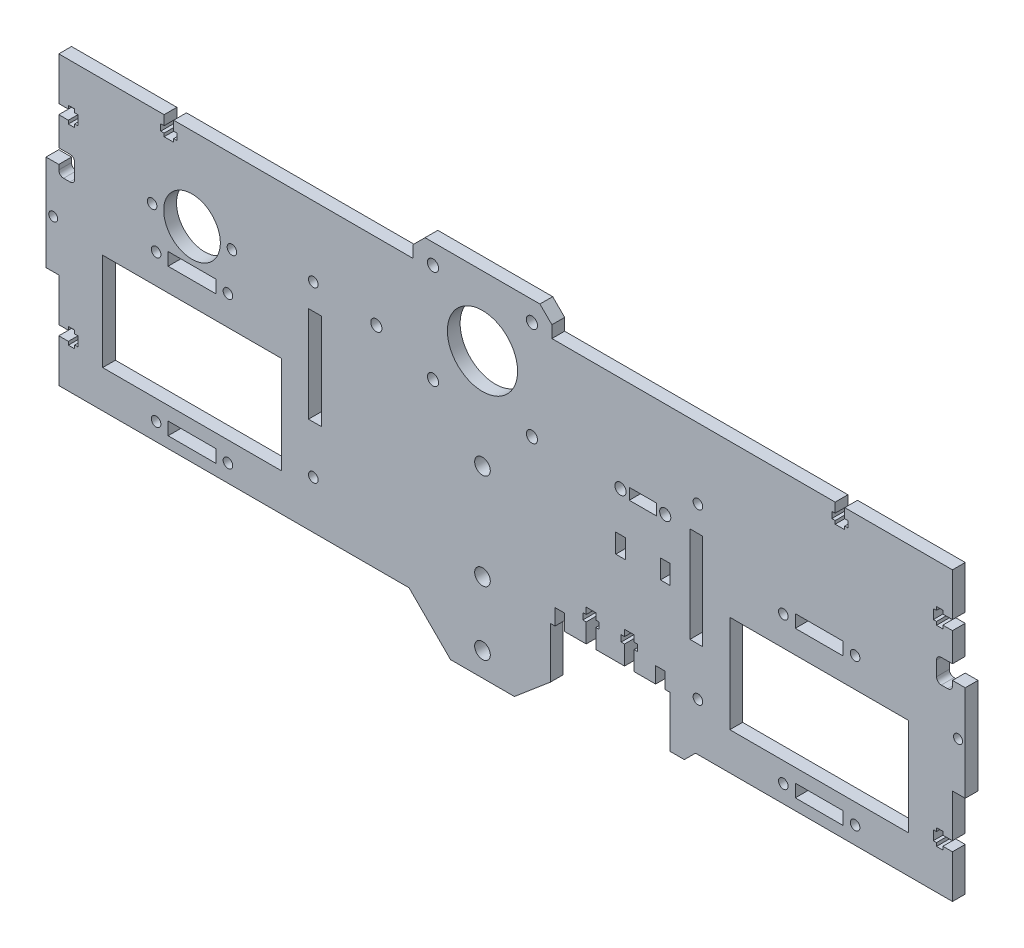
SolidWorks part; units mm, degrees
ref_plane "Спереди" through (0, 0, 0) normal (0, 0, 1) x (1, 0, 0)
ref_plane "Сверху" through (0, 0, 0) normal (0, 1, 0) x (1, 0, 0)
ref_plane "Справа" through (0, 0, 0) normal (1, 0, 0) x (0, 0, -1)
sketch "Эскиз1" plane through (0, 0, 0) normal (0, 0, 1) x (1, 0, 0)
  line L0 (81, 40.75) -> (76.5, 36.25) construction
  line L1 (-140, -45) -> (140, -45)
  line L2 (-140, -45) -> (-140, 45)
  line L3 (-140, 45) -> (140, 45)
  line L4 (140, -45) -> (140, 45)
  line L5 (-140, -45) -> (140, 45) construction
  line L6 (-140, 45) -> (140, -45) construction
  line L7 (-105.75, -37.5) -> (-90.75, -37.5)
  line L8 (-105.75, -37.5) -> (-105.75, -41.5)
  line L9 (-105.75, -41.5) -> (-90.75, -41.5)
  line L10 (-90.75, -37.5) -> (-90.75, -41.5)
  line L11 (-105.75, -37.5) -> (-90.75, -41.5) construction
  line L12 (-105.75, -41.5) -> (-90.75, -37.5) construction
  line L13 (-105.75, 4.5) -> (-90.75, 4.5)
  line L14 (-105.75, 4.5) -> (-105.75, 8.5)
  line L15 (-105.75, 8.5) -> (-90.75, 8.5)
  line L16 (-90.75, 4.5) -> (-90.75, 8.5)
  line L17 (-105.75, 4.5) -> (-90.75, 8.5) construction
  line L18 (-105.75, 8.5) -> (-90.75, 4.5) construction
  line L19 (-126.25, -33.25) -> (-70.25, -33.25)
  line L20 (-126.25, -33.25) -> (-126.25, -2.75)
  line L21 (-126.25, -2.75) -> (-70.25, -2.75)
  line L22 (-70.25, -33.25) -> (-70.25, -2.75)
  line L23 (-126.25, -33.25) -> (-70.25, -2.75) construction
  line L24 (-126.25, -2.75) -> (-70.25, -33.25) construction
  line L25 (115.5, -2.75) -> (81, -2.75) construction
  line L26 (120, 1.75) -> (120, 36.25) construction
  line L27 (115.5, 40.75) -> (81, 40.75) construction
  line L28 (76.5, 1.75) -> (76.5, 36.25) construction
  line L29 (120, -2.75) -> (76.5, 40.75) construction
  line L30 (120, 40.75) -> (76.5, -2.75) construction
  line L31 (120, 36.25) -> (115.5, 40.75) construction
  line L32 (120, 1.75) -> (115.5, -2.75) construction
  line L33 (81, -2.75) -> (76.5, 1.75) construction
  line L34 (0, -55) -> (0, 55) construction
  line L35 (126.25, -2.75) -> (70.25, -33.25) construction
  line L36 (126.25, -33.25) -> (70.25, -2.75) construction
  line L37 (105.75, 8.5) -> (90.75, 4.5) construction
  line L38 (105.75, 4.5) -> (90.75, 8.5) construction
  line L39 (105.75, -41.5) -> (90.75, -37.5) construction
  line L40 (105.75, -37.5) -> (90.75, -41.5) construction
  line L41 (70.25, -33.25) -> (70.25, -2.75)
  line L42 (126.25, -2.75) -> (70.25, -2.75)
  line L43 (126.25, -33.25) -> (126.25, -2.75)
  line L44 (126.25, -33.25) -> (70.25, -33.25)
  line L45 (90.75, 4.5) -> (90.75, 8.5)
  line L46 (105.75, 8.5) -> (90.75, 8.5)
  line L47 (105.75, 4.5) -> (105.75, 8.5)
  line L48 (105.75, 4.5) -> (90.75, 4.5)
  line L49 (90.75, -37.5) -> (90.75, -41.5)
  line L50 (105.75, -41.5) -> (90.75, -41.5)
  line L51 (105.75, -37.5) -> (105.75, -41.5)
  line L52 (105.75, -37.5) -> (90.75, -37.5)
  line L53 (-109.5, 6.5) -> (-87, 6.5) construction
  line L54 (-109.5, -39.5) -> (-87, -39.5) construction
  line L55 (135, 12) -> (135, 19.5)
  line L56 (-140, 12) -> (-135, 12)
  line L57 (-140, 12) -> (-140, 19.5)
  line L58 (-140, 19.5) -> (-135, 19.5)
  line L59 (-135, 12) -> (-135, 19.5)
  line L61 (102.2, 40) -> (107.3, 40) construction
  line L62 (102.2, 40) -> (102.2, 42) construction
  line L63 (107.3, 40) -> (107.3, 42) construction
  line L64 (102.2, 42) -> (107.3, 42) construction
  line L66 (-135, -27.45) -> (-135, -28.5) construction
  line L67 (-135, -28.5) -> (-134, -28.5) construction
  line L68 (-134, -28.5) -> (-134, -31.5) construction
  line L69 (-134, -31.5) -> (-135, -31.5) construction
  line L70 (-135, -31.5) -> (-135, -32.55) construction
  line L71 (-135, -32.55) -> (-137, -32.55) construction
  line L72 (-137, -32.55) -> (-137, -31.5) construction
  line L73 (-137, -31.5) -> (-140, -31.5) construction
  line L74 (-140, -31.5) -> (-140, -45) construction
  line L75 (-140, -45) -> (140, -45) construction
  line L76 (140, -45) -> (140, -31.5) construction
  line L77 (140, -31.5) -> (137, -31.5) construction
  line L78 (137, -31.5) -> (137, -32.55) construction
  line L79 (137, -32.55) -> (135, -32.55) construction
  line L80 (135, -32.55) -> (135, -31.5) construction
  line L81 (135, -31.5) -> (134, -31.5) construction
  line L82 (134, -31.5) -> (134, -28.5) construction
  line L83 (134, -28.5) -> (135, -28.5) construction
  line L84 (135, -28.5) -> (135, -27.45) construction
  line L85 (135, -27.45) -> (137, -27.45) construction
  line L86 (137, -27.45) -> (137, -28.5) construction
  line L87 (137, -28.5) -> (140, -28.5) construction
  line L88 (140, -28.5) -> (140, -15) construction
  line L89 (140, -15) -> (144, -15) construction
  line L90 (144, -15) -> (144, 15) construction
  line L91 (144, 15) -> (140, 15) construction
  line L92 (140, 15) -> (140, 28.5) construction
  line L93 (140, 28.5) -> (137, 28.5) construction
  line L94 (137, 28.5) -> (137, 27.45) construction
  line L95 (137, 27.45) -> (135, 27.45) construction
  line L96 (135, 27.45) -> (135, 28.5) construction
  line L97 (135, 28.5) -> (134, 28.5) construction
  line L98 (134, 28.5) -> (134, 31.5) construction
  line L99 (134, 31.5) -> (135, 31.5) construction
  line L100 (135, 31.5) -> (135, 32.55) construction
  line L101 (135, 32.55) -> (137, 32.55) construction
  line L102 (137, 32.55) -> (137, 31.5) construction
  line L103 (137, 31.5) -> (140, 31.5) construction
  line L105 (140, 19.5) -> (135, 19.5)
  line L120 (103.25, 45) -> (106.25, 45) construction
  line L122 (-108.05, 40) -> (-102.95, 40) construction
  line L124 (-108.05, 40) -> (-108.05, 42) construction
  line L136 (-102.95, 40) -> (-102.95, 42) construction
  line L148 (140, 12) -> (140, 19.5)
  line L151 (-140, 31.5) -> (-137, 31.5) construction
  line L152 (-137, 31.5) -> (-137, 32.55) construction
  line L153 (-137, 32.55) -> (-135, 32.55) construction
  line L154 (-135, 32.55) -> (-135, 31.5) construction
  line L155 (-135, 31.5) -> (-134, 31.5) construction
  line L156 (-134, 31.5) -> (-134, 28.5) construction
  line L157 (-134, 28.5) -> (-135, 28.5) construction
  line L158 (-135, 28.5) -> (-135, 27.45) construction
  line L159 (-135, 27.45) -> (-137, 27.45) construction
  line L160 (-137, 27.45) -> (-137, 28.5) construction
  line L161 (-137, 28.5) -> (-140, 28.5) construction
  line L162 (-140, 28.5) -> (-140, 15) construction
  line L163 (-140, 15) -> (-144, 15) construction
  line L164 (-144, 15) -> (-144, -15) construction
  line L165 (-144, -15) -> (-140, -15) construction
  line L166 (-140, -15) -> (-140, -28.5) construction
  line L167 (-140, -28.5) -> (-137, -28.5) construction
  line L168 (-137, -28.5) -> (-137, -27.45) construction
  line L169 (-137, -27.45) -> (-135, -27.45) construction
  line L170 (14.5, 12.75) -> (14.5, 48.75)
  line L171 (10.75, 9) -> (14.5, 12.75)
  line L172 (-25.25, 9) -> (10.75, 9)
  line L173 (-29, 12.75) -> (-25.25, 9)
  line L174 (-29, 12.75) -> (-29, 48.75)
  line L175 (10.75, 52.5) -> (14.5, 48.75)
  line L176 (-25.25, 52.5) -> (10.75, 52.5)
  line L177 (-29, 48.75) -> (-25.25, 52.5)
  line L178 (-107, 45) -> (-104, 45) construction
  line L180 (-108.05, 42) -> (-102.95, 42) construction
  line L181 (-135, -27.45) -> (-135, -28.5)
  line L182 (-135, -28.5) -> (-134, -28.5)
  line L183 (-134, -28.5) -> (-134, -31.5)
  line L184 (-134, -31.5) -> (-135, -31.5)
  line L185 (-135, -31.5) -> (-135, -32.55)
  line L186 (-135, -32.55) -> (-137, -32.55)
  line L187 (-137, -32.55) -> (-137, -31.5)
  line L188 (-137, -31.5) -> (-140, -31.5)
  line L189 (-140, -31.5) -> (-140, -45)
  line L190 (-140, -45) -> (140, -45)
  line L191 (140, -45) -> (140, -31.5)
  line L192 (140, -31.5) -> (137, -31.5)
  line L193 (137, -31.5) -> (137, -32.55)
  line L194 (137, -32.55) -> (135, -32.55)
  line L195 (135, -32.55) -> (135, -31.5)
  line L196 (135, -31.5) -> (134, -31.5)
  line L197 (134, -31.5) -> (134, -28.5)
  line L198 (134, -28.5) -> (135, -28.5)
  line L199 (135, -28.5) -> (135, -27.45)
  line L200 (135, -27.45) -> (137, -27.45)
  line L201 (137, -27.45) -> (137, -28.5)
  line L202 (137, -28.5) -> (140, -28.5)
  line L203 (140, -28.5) -> (140, -15)
  line L204 (140, -15) -> (144, -15)
  line L205 (144, -15) -> (144, 15)
  line L206 (144, 15) -> (140, 15)
  line L207 (140, 15) -> (140, 28.5)
  line L208 (140, 28.5) -> (137, 28.5)
  line L209 (137, 28.5) -> (137, 27.45)
  line L210 (137, 27.45) -> (135, 27.45)
  line L211 (135, 27.45) -> (135, 28.5)
  line L212 (135, 28.5) -> (134, 28.5)
  line L213 (134, 28.5) -> (134, 31.5)
  line L214 (134, 31.5) -> (135, 31.5)
  line L215 (135, 31.5) -> (135, 32.55)
  line L216 (135, 32.55) -> (137, 32.55)
  line L217 (137, 32.55) -> (137, 31.5)
  line L218 (137, 31.5) -> (140, 31.5)
  line L266 (-140, 31.5) -> (-137, 31.5)
  line L267 (-137, 31.5) -> (-137, 32.55)
  line L268 (-137, 32.55) -> (-135, 32.55)
  line L269 (-135, 32.55) -> (-135, 31.5)
  line L270 (-135, 31.5) -> (-134, 31.5)
  line L271 (-134, 31.5) -> (-134, 28.5)
  line L272 (-134, 28.5) -> (-135, 28.5)
  line L273 (-135, 28.5) -> (-135, 27.45)
  line L274 (-135, 27.45) -> (-137, 27.45)
  line L275 (-137, 27.45) -> (-137, 28.5)
  line L276 (-137, 28.5) -> (-140, 28.5)
  line L277 (-140, 28.5) -> (-140, 15)
  line L278 (-140, 15) -> (-144, 15)
  line L279 (-144, 15) -> (-144, -15)
  line L280 (-144, -15) -> (-140, -15)
  line L281 (-140, -15) -> (-140, -28.5)
  line L282 (-140, -28.5) -> (-137, -28.5)
  line L283 (-137, -28.5) -> (-137, -27.45)
  line L284 (-137, -27.45) -> (-135, -27.45)
  line L286 (-131, 31.5) -> (-131, 28.5)
  line L288 (131, 31.5) -> (131, 28.5)
  line L290 (103.25, 39) -> (106.25, 39)
  line L291 (102.2, 40) -> (107.3, 40)
  line L292 (102.2, 40) -> (102.2, 42)
  line L293 (107.3, 40) -> (107.3, 42)
  line L294 (102.2, 42) -> (107.3, 42)
  line L295 (103.25, 45) -> (103.25, 39)
  line L296 (103.25, 45) -> (106.25, 45)
  line L297 (106.25, 45) -> (106.25, 39)
  line L298 (-108.05, 40) -> (-102.95, 40)
  line L299 (-108.05, 40) -> (-108.05, 42)
  line L300 (-7.25, 52.5) -> (-7.25, 9) construction
  line L310 (-107, 39) -> (-104, 39)
  line L311 (-102.95, 40) -> (-102.95, 42)
  line L312 (-107, 45) -> (-104, 45)
  line L314 (-104, 45) -> (-104, 39)
  line L315 (-108.05, 42) -> (-102.95, 42)
  line L316 (-107, 45) -> (-107, 39)
  line L317 (140, 12) -> (135, 12)
  circle A8 centre (98.25, 19) radius 6 construction
  circle A9 centre (-98.25, 19) radius 8.875
  circle A10 centre (-85.75, 19) radius 1.5
  circle A11 centre (-110.75, 19) radius 1.5
  circle A15 centre (-141.75, 0) radius 1.4
  circle A16 centre (141.75, 0) radius 1.4
  circle A17 centre (-40.5, 21.1) radius 1.75
  circle A26 centre (-87, 6.5) radius 1.5
  circle A27 centre (-109.5, 6.5) radius 1.5
  circle A28 centre (-109.5, -39.5) radius 1.5
  circle A29 centre (-87, -39.5) radius 1.5
  circle A30 centre (87, -39.5) radius 1.5
  circle A31 centre (109.5, -39.5) radius 1.5
  circle A32 centre (109.5, 6.5) radius 1.5
  circle A33 centre (87, 6.5) radius 1.5
  point P0 (0, 0)
  point P5 (-98.25, -39.5)
  point P11 (-98.25, 6.5)
  point P16 (-98.25, -18)
  point P28 (98.25, 19)
  point P54 (-98.25, 6.5)
  point P58 (-98.25, -2.75)
  point P63 (98.25, -18)
  point P64 (98.25, 6.5)
  point P65 (98.25, -39.5)
  point P66 (-98.25, -39.5)
  point P159 (-144, 0)
  point P175 (-40.5, -35.103)
  dimension "D10" = 3
  dimension "D23" = 2
  dimension "D24" = 12
  dimension "D25" = 17.75
  dimension "D30" = 3
  dimension "D32" = 9
  dimension "D33" = 23.9
  dimension "D44" = 2.8
  dimension "D34" = 3.5
  dimension "D1" = 280
  dimension "D2" = 90
  dimension "D3" = 3.5
  dimension "D4" = 15
  dimension "D5" = 4
  dimension "D6" = 42
  dimension "D7" = 11.75
  dimension "D8" = 30.5
  dimension "D9" = 56
  dimension "D11" = 43.5
  dimension "D12" = 4.5
  dimension "D13" = 4.5
  dimension "D14" = 4.5
  dimension "D15" = 4.5
  dimension "D16" = 4.5
  dimension "D17" = 4.5
  dimension "D18" = 4.5
  dimension "D19" = 4.5
  dimension "D20" = 64
  dimension "D21" = 98.25
  dimension "D22" = 22.5
  dimension "D26" = 22.5
  dimension "D27" = 2
  dimension "D28" = 98.25
  dimension "D29" = 12.5
  dimension "D31" = 12.5
  dimension "D35" = 36
  dimension "D36" = 36
  dimension "D37" = 3.75
  dimension "D38" = 3.75
  dimension "D39" = 29
  dimension "D40" = 9
  dimension "D41" = 5
  dimension "D42" = 7.5
  dimension "D43" = 3
  dimension "D45" = 2.25
  dimension "D46" = 6
extrude "Бобышка-Вытянуть1" add sketch "Эскиз1" along normal blind 4 contours L316 L3 L2 L266 L267 L268 L269 L270 L271 L272 L273 L274 L275 L276 L282 L283 L284 L181 L182 L20 L21 L22 L19 L184 L185 L186 L187 L188 L1 L4 L192 L193 L194 L195 L196 L43 L44 L41 L42 L198 | L177 L174 L3 L170 L175 L176 | L174 L173 L172 L171 L170 L3 | L205 L206 L4 L204 | L279 L280 L2 L278
sketch "Эскиз2" plane through (0, 0, 4) normal (0, 0, 1) x (1, 0, 0)
  line L0 (140, 45) -> (144, 45) construction
  line L1 (144, 45) -> (144, 15) construction
  line L2 (140, 45) -> (140, 15) construction
  line L54 (69.5, 45) -> (69.5, 49) construction
  line L60 (69.5, 45) -> (89.5, 45) construction
  line L62 (140, 15) -> (144, 15) construction
  line L63 (144, 15) -> (140, 15) construction
  line L64 (144, 15) -> (144, -15) construction
  line L65 (140, 15) -> (140, -15) construction
  line L67 (69.5, 49) -> (89.5, 49) construction
  line L73 (89.5, 45) -> (89.5, 49) construction
  line L75 (140, -15) -> (144, -15) construction
  line L76 (140, -45) -> (140, -15) construction
  line L77 (140, -45) -> (144, -45) construction
  line L78 (144, -45) -> (144, -15) construction
  line L79 (144, -15) -> (140, -15) construction
  line L80 (-140, 45) -> (-140, 15) construction
  line L81 (-144, 45) -> (-144, 15) construction
  line L82 (-140, 45) -> (-144, 45) construction
  line L83 (-140, 15) -> (-144, 15) construction
  line L84 (-144, 15) -> (-140, 15) construction
  line L85 (-140, 15) -> (-140, -15) construction
  line L86 (-144, 15) -> (-144, -15) construction
  line L87 (-140, -15) -> (-144, -15) construction
  line L88 (-144, -45) -> (-144, -15) construction
  line L89 (-140, -45) -> (-144, -45) construction
  line L90 (-140, -45) -> (-140, -15) construction
  line L91 (-144, -15) -> (-140, -15) construction
  line L92 (140, 45) -> (144, 45)
  line L93 (144, 45) -> (144, 15)
  line L94 (140, 45) -> (140, 15)
  line L106 (140, 15) -> (144, 15)
  line L107 (144, 15) -> (140, 15)
  line L108 (144, 15) -> (144, -15)
  line L109 (140, 15) -> (140, -15)
  line L119 (140, -15) -> (144, -15)
  line L120 (140, -45) -> (140, -15)
  line L121 (140, -45) -> (144, -45)
  line L122 (144, -45) -> (144, -15)
  line L123 (144, -15) -> (140, -15)
  line L124 (-140, 45) -> (-140, 15)
  line L125 (-144, 45) -> (-144, 15)
  line L126 (-140, 45) -> (-144, 45)
  line L127 (-140, 15) -> (-144, 15)
  line L128 (-144, 15) -> (-140, 15)
  line L129 (-140, 15) -> (-140, -15)
  line L130 (-144, 15) -> (-144, -15)
  line L131 (-140, -15) -> (-144, -15)
  line L132 (-144, -45) -> (-144, -15)
  line L133 (-140, -45) -> (-144, -45)
  line L134 (-140, -45) -> (-140, -15)
  line L135 (-144, -15) -> (-140, -15)
  line L136 (120, 45) -> (120, 49) construction
  line L137 (140, 45) -> (120, 45) construction
  line L138 (140, 45) -> (140, 49) construction
  line L139 (140, 49) -> (120, 49) construction
  line L140 (-140, 45) -> (-140, 49) construction
  line L141 (-140, 45) -> (-120, 45) construction
  line L142 (-120, 45) -> (-120, 49) construction
  line L143 (-140, 49) -> (-120, 49) construction
  line L144 (-71, 45) -> (-71, 49) construction
  line L145 (-71, 49) -> (-91, 49) construction
  line L146 (-91, 45) -> (-91, 49) construction
  line L147 (-71, 45) -> (-91, 45) construction
  line L148 (69.5, 45) -> (69.5, 49)
  line L149 (69.5, 45) -> (89.5, 45)
  line L150 (69.5, 49) -> (89.5, 49)
  line L151 (89.5, 45) -> (89.5, 49)
  line L152 (120, 45) -> (120, 49)
  line L153 (140, 45) -> (120, 45)
  line L154 (140, 45) -> (140, 49)
  line L155 (140, 49) -> (120, 49)
  line L156 (-140, 45) -> (-140, 49)
  line L157 (-140, 45) -> (-120, 45)
  line L158 (-120, 45) -> (-120, 49)
  line L159 (-140, 49) -> (-120, 49)
  line L160 (-71, 45) -> (-71, 49)
  line L161 (-71, 49) -> (-91, 49)
  line L162 (-91, 45) -> (-91, 49)
  line L163 (-71, 45) -> (-91, 45)
  circle A17 centre (-141.75, -30) radius 1.4
  circle A18 centre (-141.75, -30) radius 1.4
  circle A19 centre (141.75, -30) radius 1.4
  circle A20 centre (141.75, -30) radius 1.4
  circle A21 centre (141.75, 30) radius 1.4
  circle A22 centre (141.75, 30) radius 1.4
  circle A23 centre (-141.75, 0) radius 1.4
  circle A24 centre (-141.75, 0) radius 1.4
  circle A29 centre (-141.75, 30) radius 1.4
  circle A30 centre (-141.75, 30) radius 1.4
  circle A35 centre (141.75, 0) radius 1.4
  circle A36 centre (141.75, 0) radius 1.4
  circle A142 centre (79.5, 46.75) radius 1.4 construction
  circle A143 centre (130, 46.75) radius 1.4 construction
  circle A144 centre (-130, 46.75) radius 1.4 construction
  circle A145 centre (-81, 46.75) radius 1.4 construction
  circle A146 centre (79.5, 46.75) radius 1.4
  circle A147 centre (130, 46.75) radius 1.4
  circle A148 centre (-130, 46.75) radius 1.4
  circle A149 centre (-81, 46.75) radius 1.4
  dimension "D5" = 0
  dimension "D6" = 0
  dimension "D7" = 0
  dimension "D8" = 0
  dimension "D11" = 0
  dimension "D14" = 0
extrude "Бобышка-Вытянуть2" add sketch "Эскиз2" against normal through all
sketch "Эскиз3" plane through (0, 0, 4) normal (0, 0, 1) x (1, 0, 0)
  line L0 (-25.25, 52.5) -> (10.75, 52.5) construction
  line L1 (-140, -45) -> (140, -45) construction
  line L4 (140, -45) -> (140, -31.5) construction
  line L18 (-22.75, 46.25) -> (8.25, 46.25) construction
  line L19 (-22.75, 46.25) -> (-22.75, 15.25) construction
  line L20 (-22.75, 15.25) -> (8.25, 15.25) construction
  line L21 (8.25, 46.25) -> (8.25, 15.25) construction
  line L24 (14, -45) -> (51.5, -45)
  line L25 (14, -45) -> (14, -32.5)
  line L26 (14, -32.5) -> (51.5, -32.5)
  line L27 (51.5, -45) -> (51.5, -32.5)
  line L32 (18.5, -32.5) -> (18.5, -27.5)
  line L33 (50, -32.5) -> (47, -32.5)
  line L35 (50, -32.5) -> (50, -27.5)
  line L36 (50, -27.5) -> (47, -27.5)
  line L39 (47, -32.5) -> (47, -27.5)
  line L40 (15.5, -27.5) -> (18.5, -27.5)
  line L41 (32.75, -32.5) -> (32.75, -19.9047) construction
  line L42 (25.25, -32.5) -> (28.25, -32.5)
  line L43 (25.25, -32.5) -> (25.25, -22.5)
  line L44 (25.25, -22.5) -> (28.25, -22.5)
  line L45 (28.25, -32.5) -> (28.25, -22.5)
  line L46 (24.2, -26.5) -> (29.3, -26.5)
  line L47 (24.2, -26.5) -> (24.2, -24.5)
  line L48 (24.2, -24.5) -> (29.3, -24.5)
  line L49 (29.3, -26.5) -> (29.3, -24.5)
  line L50 (24.2, -26.5) -> (29.3, -24.5) construction
  line L51 (24.2, -24.5) -> (29.3, -26.5) construction
  line L52 (41.3, -24.5) -> (36.2, -26.5) construction
  line L53 (41.3, -26.5) -> (36.2, -24.5) construction
  line L54 (36.2, -26.5) -> (36.2, -24.5)
  line L55 (41.3, -24.5) -> (36.2, -24.5)
  line L56 (41.3, -26.5) -> (41.3, -24.5)
  line L57 (41.3, -26.5) -> (36.2, -26.5)
  line L58 (37.25, -32.5) -> (37.25, -22.5)
  line L59 (40.25, -22.5) -> (37.25, -22.5)
  line L60 (40.25, -32.5) -> (40.25, -22.5)
  line L61 (40.25, -32.5) -> (37.25, -32.5)
  line L62 (15.5, -32.5) -> (15.5, -27.5)
  line L63 (15.5, -32.5) -> (18.5, -32.5)
  circle A4 centre (8.25, 15.25) radius 1.75
  circle A5 centre (-22.75, 15.25) radius 1.75
  circle A6 centre (8.25, 46.25) radius 1.75
  circle A7 centre (-22.75, 46.25) radius 1.75
  circle A11 centre (-7.25, 30.75) radius 11
  point P2 (-7.25, 52.5)
  point P36 (-7.25, 46.25)
  point P45 (8.25, 30.75)
  point P81 (26.75, -22.5)
  point P83 (26.75, -25.5)
  point P103 (38.75, -25.5)
  dimension "D5" = 3.5
  dimension "D7" = 22
  dimension "D3" = 88.5
  dimension "D4" = 6.25
  dimension "D6" = 31
  dimension "D9" = 37.5
  dimension "D10" = 12.5
  dimension "D12" = 3
  dimension "D13" = 10
  dimension "D14" = 2
  dimension "D15" = 5.1
  dimension "D16" = 2
  dimension "D17" = 4.5
  dimension "D18" = 5
  dimension "D19" = 3
  dimension "D20" = 1.5
extrude "Вырез-Вытянуть1" cut sketch "Эскиз3" against normal through all
sketch "Эскиз4" plane through (0, 0, 4) normal (0, 0, 1) x (1, 0, 0)
  line L0 (2.75, 6.5) -> (2.75, -60.5) construction
  line L1 (2.75, -45) -> (-17.25, -45)
  line L2 (2.75, -45) -> (2.75, -58)
  line L3 (2.75, -58) -> (-17.25, -58)
  line L4 (-17.25, -45) -> (-17.25, -58)
  line L6 (14, -48.5) -> (2.75, -58)
  line L7 (14, -45) -> (9.5, -45)
  line L8 (14, -45) -> (14, -48.5)
  line L9 (14, -48.5) -> (9.5, -48.5)
  line L10 (9.5, -45) -> (9.5, -48.5)
  line L11 (9.5, -45) -> (2.75, -45)
  line L12 (-140, -45) -> (14, -45) construction
  line L13 (51.5, -45) -> (140, -45) construction
  line L14 (56, -45) -> (56, -48.5)
  line L15 (51.5, -48.5) -> (56, -48.5)
  line L16 (51.5, -45) -> (51.5, -48.5)
  line L17 (51.5, -45) -> (56, -45)
  line L18 (56, -48.5) -> (59.5, -45)
  line L20 (-17.25, -58) -> (-30.25, -45)
  line L21 (-17.25, -45) -> (-30.25, -45)
  line L22 (59.5, -45) -> (51.5, -45)
  circle A1 centre (-7.25, -50.5) radius 2.45
  dimension "D1" = 45
  dimension "D2" = 45
  dimension "D3" = 5.5
  dimension "D4" = 13
  dimension "D5" = 20
extrude "Бобышка-Вытянуть3" add sketch "Эскиз4" against normal through all contours L1 L4 L3 L2 | L10 L11 L2 L6 L9 | L7 L10 L9 L8 | L17 L16 L15 L14 | L18 L22 L14 | L4 L21 L20
sketch "Эскиз5" plane through (0, 0, 4) normal (0, 0, 1) x (1, 0, 0)
  line L0 (-140, -45) -> (-30.25, -45) construction
  line L1 (140, 1.5) -> (140, 15) construction
  line L2 (36, 15) -> (50, 15) construction
  line L3 (38.75, 13.25) -> (47.25, 13.25)
  line L4 (38.75, 13.25) -> (38.75, 16.75)
  line L5 (38.75, 16.75) -> (47.25, 16.75)
  line L6 (47.25, 13.25) -> (47.25, 16.75)
  line L7 (38.75, 13.25) -> (47.25, 16.75) construction
  line L8 (38.75, 16.75) -> (47.25, 13.25) construction
  line L9 (-59.75, 45) -> (-59.75, 15) construction
  line L11 (-59.75, 15) -> (-59.75, -15) construction
  line L12 (-59.75, -15) -> (-59.75, -45) construction
  line L13 (34.5, -3.5) -> (37.5, -3.5)
  line L14 (-59.75, 45) -> (-59.75, 35) construction
  line L15 (-59.75, 35) -> (-59.75, 25) construction
  line L16 (-59.75, 25) -> (-59.75, 15) construction
  line L17 (-61.75, 0) -> (-57.75, 0) construction
  line L18 (-61.75, -15) -> (-57.75, -15)
  line L19 (-61.75, -15) -> (-61.75, 15)
  line L20 (-61.75, 15) -> (-57.75, 15)
  line L21 (-57.75, -15) -> (-57.75, 15)
  line L22 (-61.75, -15) -> (-57.75, 15) construction
  line L23 (-61.75, 15) -> (-57.75, -15) construction
  line L24 (-66.75, -14.5) -> (-66.75, -10.8) construction
  line L25 (0, 0) -> (0, 20.9914) construction
  line L26 (61.75, 15) -> (57.75, -15) construction
  line L27 (61.75, -15) -> (57.75, 15) construction
  line L28 (61.75, 0) -> (57.75, 0) construction
  line L32 (59.5, -45) -> (140, -45) construction
  line L33 (59.75, 15) -> (59.75, -15) construction
  line L35 (57.75, -15) -> (57.75, 15)
  line L36 (61.75, 15) -> (57.75, 15)
  line L37 (61.75, -15) -> (61.75, 15)
  line L38 (61.75, -15) -> (57.75, -15)
  line L39 (0, -2.2) -> (0, 2.2) construction
  line L40 (60.25, 45) -> (60.25, 15) construction
  line L41 (2.2, 0) -> (-2.2, 0) construction
  line L42 (34.5, -3.5) -> (34.5, 2.5)
  line L43 (14.5, 45) -> (103.25, 45) construction
  line L44 (-104, 45) -> (-29, 45) construction
  line L45 (34.5, 2.5) -> (37.5, 2.5)
  line L46 (37.5, -3.5) -> (37.5, 2.5)
  line L47 (34.5, -3.5) -> (37.5, 2.5) construction
  line L48 (34.5, 2.5) -> (37.5, -3.5) construction
  line L49 (51.5, -3.5) -> (48.5, -3.5)
  line L50 (51.5, -3.5) -> (51.5, 2.5)
  line L51 (51.5, 2.5) -> (48.5, 2.5)
  line L52 (48.5, -3.5) -> (48.5, 2.5)
  line L53 (51.5, -3.5) -> (48.5, 2.5) construction
  line L54 (51.5, 2.5) -> (48.5, -3.5) construction
  circle A0 centre (-7.25, -30.5) radius 2.45 construction
  circle A1 centre (-7.25, -0.5) radius 2.45 construction
  circle A2 centre (-7.25, -30.5) radius 2.45
  circle A3 centre (-7.25, -0.5) radius 2.45
  circle A4 centre (36, 15) radius 1.75
  circle A5 centre (50, 15) radius 1.75
  circle A18 centre (60.25, 30) radius 1.5
  circle A19 centre (-60.25, 30) radius 1.5
  circle A20 centre (60.25, -30) radius 1.5
  circle A21 centre (-60.25, -30) radius 1.5
  circle A22 centre (60.25, 23) radius 1.5
  circle A23 centre (-60.25, 23) radius 1.5
  point P10 (43, 15)
  point P18 (43, 15)
  point P23 (36, -0.5)
  point P35 (-59.75, 0)
  point P66 (59.75, 0)
  point P77 (50, -0.5)
  dimension "D2" = 3.5
  dimension "D8" = 2.5
  dimension "D13" = 8
  dimension "D12" = 3
  dimension "D1" = 14
  dimension "D3" = 60
  dimension "D4" = 90
  dimension "D5" = 8.5
  dimension "D6" = 3.5
  dimension "D7" = 12.5
  dimension "D9" = 4
  dimension "D10" = 30
  dimension "D11" = 5
  dimension "D14" = 6
  dimension "D15" = 3
extrude "Вырез-Вытянуть2" cut sketch "Эскиз5" against normal through all contours A3 | A2 | A21 | L18 L21 L20 L19 | A23 | A22 | L38 L37 L36 L35 | A20 | A4 | A5 | L13 L46 L45 L42 | L3 L6 L5 L4 | L52 L49 L50 L51
fillet "Скругление1" radius 1.5 6 edges at (-140, 12, 2) (-135, 19.5, 2) (-135, 12, 2) (140, 12, 2) (135, 12, 2) (135, 19.5, 2)
sketch "Эскиз6" plane through (0, 0, 4) normal (0, 0, 1) x (1, 0, 0)
  line L0 (-140, -45) -> (-30.25, -45) construction
  line L1 (-144, -45) -> (-57.75, -45)
  line L2 (-144, -45) -> (-144, -245)
  line L3 (-144, -245) -> (-57.75, -245)
  line L4 (-57.75, -45) -> (-57.75, -245)
  line L6 (-135.875, -175) -> (-65.875, -175) construction
  line L7 (-135.875, -175) -> (-135.875, -65) construction
  line L8 (-135.875, -65) -> (-65.875, -65) construction
  line L9 (-65.875, -175) -> (-65.875, -65) construction
  line L10 (-135.875, -175) -> (-65.875, -65) construction
  line L11 (-135.875, -65) -> (-65.875, -175) construction
  line L12 (-57.75, -245) -> (2.75, -245)
  line L13 (-57.75, -245) -> (-57.75, -208.5)
  line L14 (-57.75, -208.5) -> (2.75, -208.5)
  line L15 (2.75, -245) -> (2.75, -208.5)
  line L16 (-57.75, -208.5) -> (-17.25, -208.5)
  line L17 (-57.75, -208.5) -> (-57.75, -220)
  line L18 (-57.75, -220) -> (-17.25, -220)
  line L19 (-17.25, -208.5) -> (-17.25, -220)
  circle A0 centre (-135.875, -65) radius 1.75
  circle A1 centre (-65.875, -65) radius 1.75
  circle A2 centre (-65.875, -175) radius 1.75
  circle A3 centre (-135.875, -175) radius 1.75
  circle A4 centre (-7.25, -235) radius 1.75
  point P4 (-100.875, -120)
  point P18 (-100.875, -245)
  dimension "D2" = 3.5
  dimension "D12" = 3.5
  dimension "D1" = 200
  dimension "D3" = 70
  dimension "D4" = 110
  dimension "D5" = 70
  dimension "D6" = 60.5
  dimension "D7" = 36.5
  dimension "D8" = 40.5
  dimension "D9" = 25
  dimension "D10" = 10
  dimension "D11" = 10
extrude "Бобышка-Вытянуть4" [suppressed] add sketch "Эскиз6" against normal blind 4 contours L4 L1 L2 L3 L13 A3 A2 A1 A0 | L14 L19 L18 L13 L12 L15
chamfer "Фаска1" [suppressed] distance 15 angle 45
chamfer "Фаска2" [suppressed] distance 5 angle 45
